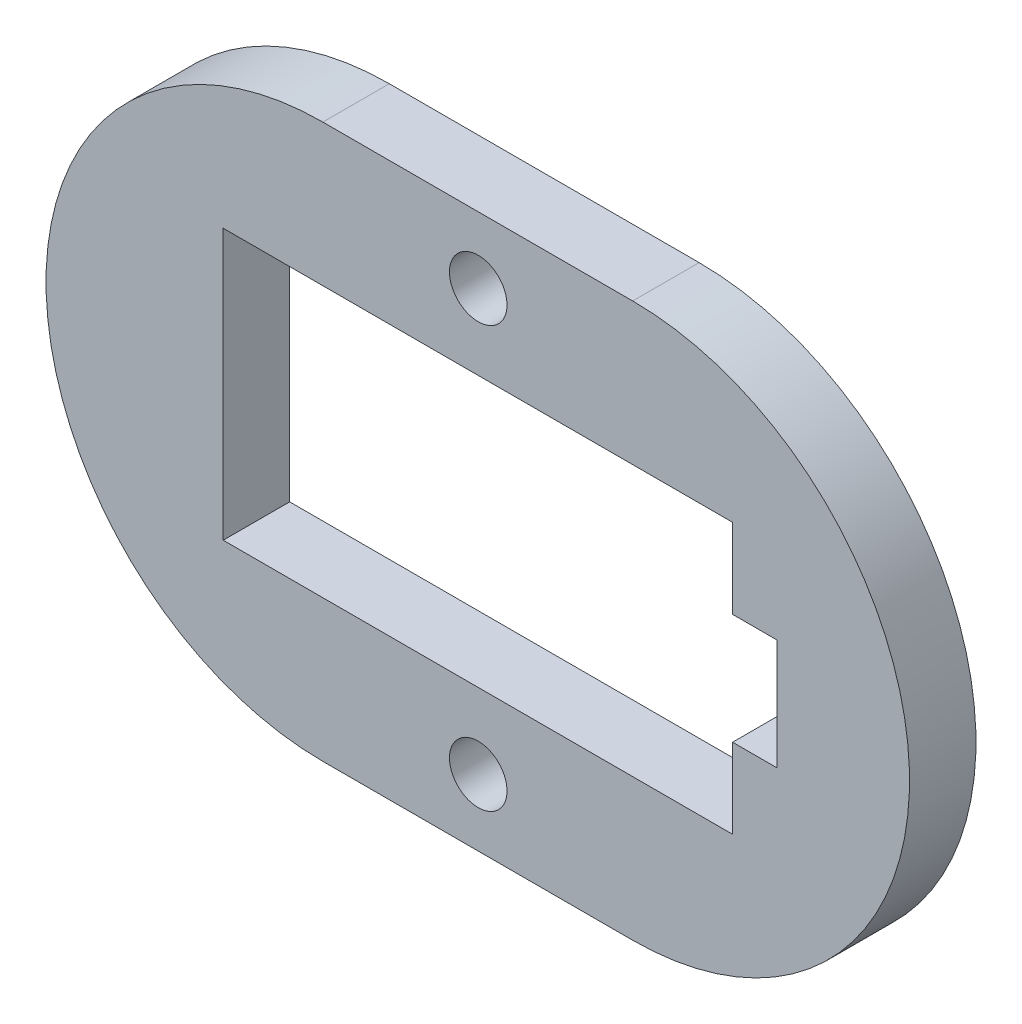
SolidWorks part; units mm, degrees
ref_plane "前视基准面" through (0, 0, 0) normal (0, 0, 1) x (1, 0, 0)
ref_plane "上视基准面" through (0, 0, 0) normal (0, 1, 0) x (1, 0, 0)
ref_plane "右视基准面" through (0, 0, 0) normal (1, 0, 0) x (0, 0, -1)
ref_plane "基准面1" through (0, 0, 3) normal (0, 0, 1) x (1, 0, 0)
sketch "草图1" plane through (0, 0, 3) normal (0, 0, 1) x (1, 0, 0)
  line L1 (-8.5033, 0.0005) -> (5.4866, 0.0005)
  line L2 (5.4866, 25.0005) -> (-8.5033, 25.0005)
  line L3 (11.9978, 15) -> (11.9978, 10.001)
  line L4 (11.9978, 10.001) -> (9.9969, 10.001)
  line L5 (9.9969, 10.001) -> (9.9969, 6.4)
  line L6 (9.9969, 6.4) -> (-13.0026, 6.4)
  line L7 (-13.0026, 6.4) -> (-13.0026, 18.6)
  line L8 (-13.0026, 18.6) -> (9.9969, 18.6)
  line L9 (9.9969, 18.6) -> (9.9969, 15)
  line L10 (9.9969, 15) -> (11.9978, 15)
  circle A0 centre (-1.4879, 2.9995) radius 1.3
  circle A1 centre (-1.4879, 22.0005) radius 1.3
  arc A3 (5.4866, 25.0005) -> (5.4866, 0.0005) centre (5.4866, 12.5005) cw
  arc A4 (-8.5033, 25.0005) -> (-8.5033, 0.0005) centre (-8.5033, 12.5005) ccw
  dimension "D1" = 12.5
  dimension "D3" = 12.5
extrude "凸台-拉伸1" add sketch "草图1" against normal blind 3
